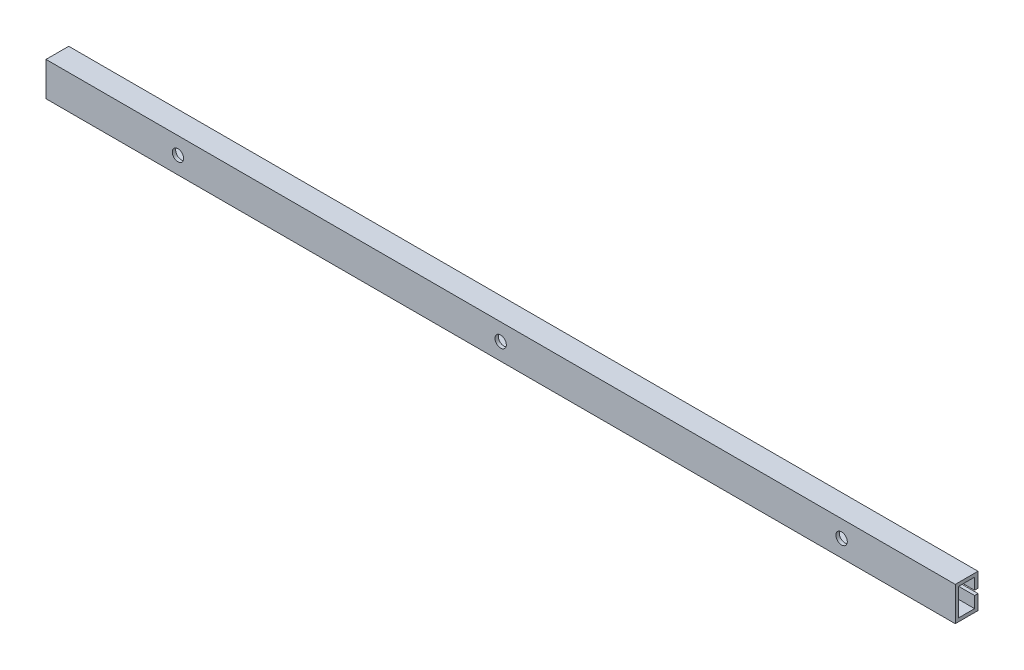
SolidWorks part; units mm, degrees
ref_plane "Alzado" through (0, 0, 0) normal (0, 0, 1) x (1, 0, 0)
ref_plane "Planta" through (0, 0, 0) normal (0, 1, 0) x (1, 0, 0)
ref_plane "Vista lateral" through (0, 0, 0) normal (1, 0, 0) x (0, 0, -1)
sketch "Croquis1" plane through (0, 0, 0) normal (0, 0, 1) x (1, 0, 0)
  line L0 (-500, 0) -> (500, 0)
  line L1 (-500, 0) -> (-500, 30)
  line L2 (-500, 30) -> (500, 30)
  line L3 (500, 30) -> (500, 0)
  point P4 (0, 0)
  dimension "D1" = 30
extrude "Saliente-Extruir1" add sketch "Croquis1" along normal blind 20
sketch "Croquis2" plane through (500, 0, 0) normal (1, 0, 0) x (0, 0, -1)
  line L0 (-17, 27) -> (-17, 3)
  line L1 (-20, 30) -> (-20, 0) construction
  line L2 (-20, 30) -> (0, 30) construction
  line L3 (-20, 0) -> (0, 0) construction
  line L4 (-17, 27) -> (-3, 27)
  line L5 (0, 30) -> (0, 0) construction
  line L6 (-3, 3) -> (-17, 3)
  line L7 (-3, 27) -> (-3, 17)
  line L8 (-3, 3) -> (-3, 12.9987)
  line L9 (-3, 17) -> (0, 17)
  line L10 (-3, 12.9987) -> (0, 12.9987)
  line L11 (0, 17) -> (0, 12.9987)
  dimension "D1" = 3
  dimension "D2" = 3
  dimension "D3" = 3
  dimension "D4" = 3
  dimension "D5" = 10
extrude "Cortar-Extruir1" cut sketch "Croquis2" against normal through all
sketch "Croquis3" plane through (0, 0, 20) normal (0, 0, 1) x (1, 0, 0)
  line L0 (-500, 30) -> (-400, 30)
  line L1 (500, 30) -> (-500, 30) construction
  line L2 (-400, 30) -> (-400, 0)
  line L3 (-500, 0) -> (500, 0) construction
  line L4 (-400, 0) -> (-500, 0)
  line L5 (-500, 0) -> (-500, 30)
  line L7 (400, 0) -> (500, 0)
  line L8 (400, 30) -> (400, 0)
  line L9 (500, 30) -> (400, 30)
  line L10 (500, 0) -> (500, 30)
  dimension "D1" = 100
extrude "Cortar-Extruir2" cut sketch "Croquis3" against normal through all
sketch "Croquis4" plane through (0, 0, 20) normal (0, 0, 1) x (1, 0, 0)
  line L0 (400, 30) -> (400, 0) construction
  line L1 (-400, 0) -> (-400, 30) construction
  circle A0 centre (300, 15) radius 5
  circle A1 centre (0, 15) radius 5
  circle A2 centre (-283.92, 15) radius 5
  dimension "D1" = 10
  dimension "D2" = 10
  dimension "D5" = 10
  dimension "D3" = 300
  dimension "D4" = 100
  dimension "D7" = 116.08
extrude "Cortar-Extruir3" cut sketch "Croquis4" against normal blind 10
